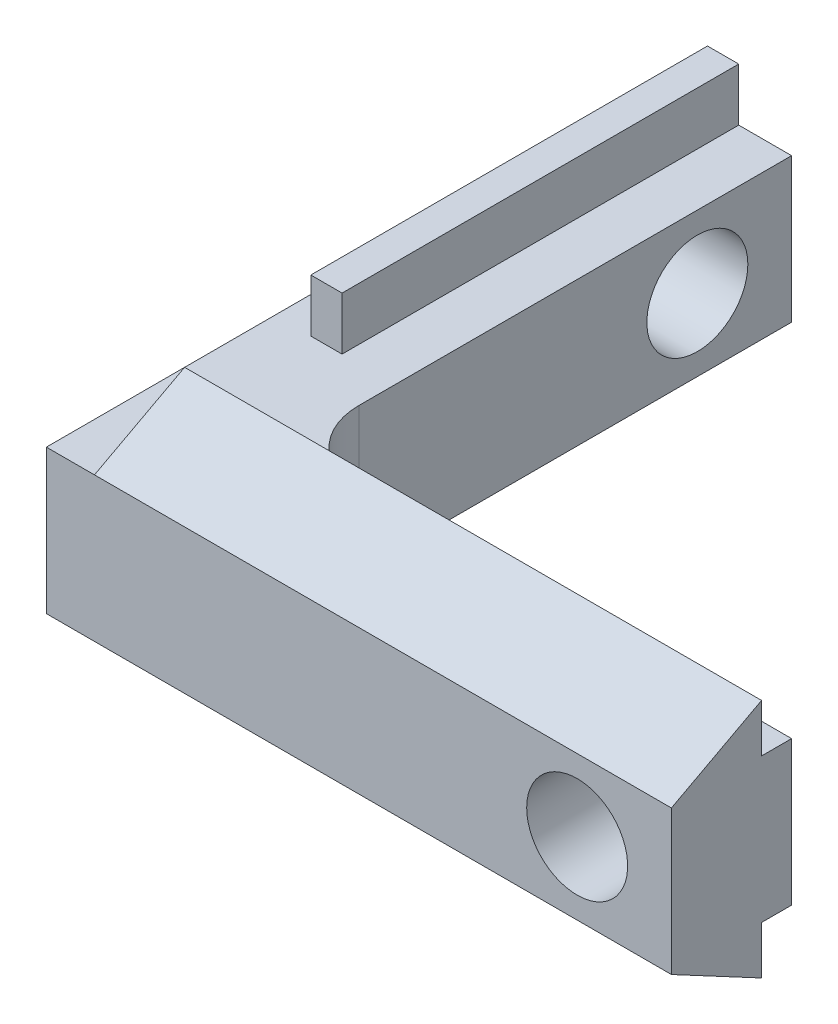
SolidWorks part; units mm, degrees
ref_plane "Front Plane" through (0, 0, 0) normal (0, 0, 1) x (1, 0, 0)
ref_plane "Top Plane" through (0, 0, 0) normal (0, 1, 0) x (1, 0, 0)
ref_plane "Right Plane" through (0, 0, 0) normal (1, 0, 0) x (0, 0, -1)
sketch "Sketch1" plane through (0, 0, 0) normal (0, 1, 0) x (1, 0, 0)
  line L0 (0, 0) -> (0, 26)
  line L1 (0, 0) -> (26, 0)
  line L2 (26, 5) -> (5, 5)
  line L3 (5, 5) -> (5, 26)
  line L4 (5, 26) -> (0, 26)
  line L5 (26, 5) -> (26, 0)
  dimension "D1" = 26
  dimension "D2" = 26
  dimension "D3" = 5
  dimension "D4" = 5
extrude "Boss-Extrude1" add sketch "Sketch1" along normal blind 6
sketch "Sketch3" plane through (0, 6, 0) normal (0, 1, 0) x (1, 0, 0)
  line L0 (5, 26) -> (2.8, 26) construction
  line L1 (5, 26) -> (0, 26) construction
  line L2 (0, 26) -> (1.5, 26) construction
  line L3 (1.5, 26) -> (1.5, 9.5)
  line L4 (2.8, 26) -> (2.8, 9.5)
  line L5 (2.8, 26) -> (1.5, 26)
  line L6 (2.8, 9.5) -> (1.5, 9.5)
  dimension "D1" = 2.2
  dimension "D2" = 1.5
  dimension "D3" = 16.5
extrude "Boss-Extrude2" add sketch "Sketch3" along normal blind 2.2
sketch "Sketch4" plane through (0, 0, 0) normal (0, -1, 0) x (1, 0, 0)
  line L1 (1.5, -26) -> (2.8, -26)
  line L2 (1.5, -26) -> (1.5, -9.5)
  line L3 (1.5, -9.5) -> (2.8, -9.5)
  line L4 (2.8, -26) -> (2.8, -9.5)
  dimension "D1" = 16.5
  dimension "D2" = 1.3
extrude "Boss-Extrude3" add sketch "Sketch4" along normal blind 2.2
sketch "Sketch5" plane through (26, 0, 0) normal (1, 0, 0) x (0, 0, -1)
  line L0 (3.75, 6) -> (3.75, 8)
  line L1 (0, 6) -> (5, 6) construction
  line L2 (3.75, 8) -> (0, 6)
  line L3 (0, 6) -> (3.75, 6)
  line L4 (5, 6) -> (5, 0) construction
  line L5 (3.75, 0) -> (3.75, -2)
  line L6 (0, 0) -> (5, 0) construction
  line L7 (3.75, -2) -> (0, 0)
  line L8 (0, 0) -> (3.75, 0)
  dimension "D1" = 1.25
  dimension "D2" = 2
  dimension "D3" = 2
extrude "Boss-Extrude4" add sketch "Sketch5" against normal blind 24
fillet "Fillet1" radius 3 1 edges at (5, 3, -5)
sketch "Sketch6" plane through (0, 0, -5) normal (0, 0, -1) x (-1, 0, 0)
  line L0 (-26, 6) -> (-26, 0) construction
  line L1 (-2, 6) -> (-26, 6) construction
  circle A0 centre (-22.079, 3) radius 2.1
  dimension "D1" = 3.921
  dimension "D2" = 4.2
  dimension "D3" = 3
extrude "Cut-Extrude1" cut sketch "Sketch6" against normal blind 24
sketch "Sketch7" plane through (5, 0, 0) normal (1, 0, 0) x (0, 0, -1)
  line L0 (9.5, 6) -> (26, 6) construction
  line L1 (26, 6) -> (26, 0) construction
  circle A0 centre (22.079, 3) radius 2.1
  dimension "D1" = 4.2
  dimension "D2" = 3
  dimension "D3" = 3.921
extrude "Cut-Extrude2" cut sketch "Sketch7" against normal blind 24
